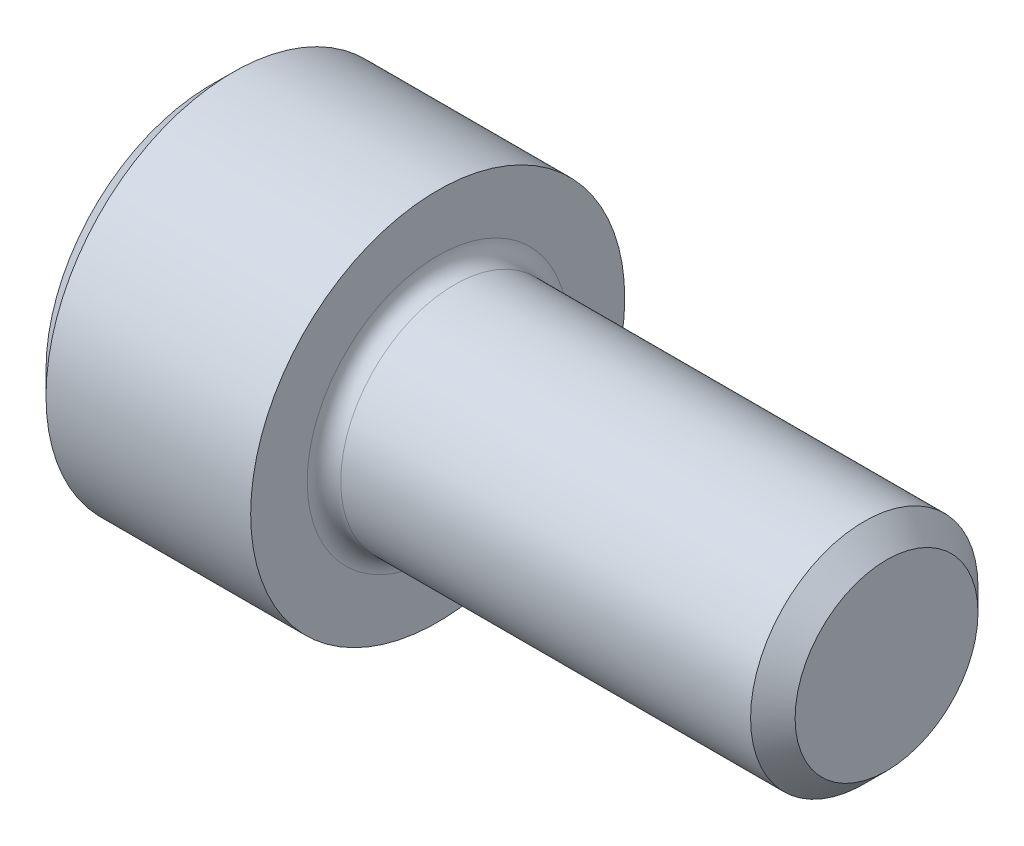
SolidWorks part; units mm, degrees
material "AISI 316 Annealed Stainless Steel Bar (SS)"
ref_plane "Plane1" through (0, 0, 0) normal (0, 0, 1) x (1, 0, 0)
ref_plane "Plane2" through (0, 0, 0) normal (0, 1, 0) x (1, 0, 0)
ref_plane "Plane3" through (0, 0, 0) normal (1, 0, 0) x (0, 0, -1)
sketch "BodySke" plane through (0, 0, 0) normal (0, 0, 1) x (1, 0, 0)
  line L0 (0, 0) -> (0, 3.4862)
  line L1 (0.4826, 3.9687) -> (4.826, 3.9687)
  line L2 (4.826, 3.9687) -> (4.826, 2.413)
  line L3 (4.826, 2.413) -> (13.8786, 2.413)
  line L4 (14.351, 1.9406) -> (14.351, 0)
  line L5 (14.351, 0) -> (0, 0)
  line L6 (-31.75, 0) -> (127, 0) construction
  line L7 (0, 3.4862) -> (0.4826, 3.9687)
  line L8 (14.351, 1.9406) -> (13.8786, 2.413)
  line L9 (0, -3.4862) -> (0.4826, -3.9688) construction
  line L10 (14.351, -1.9406) -> (13.8786, -2.413) construction
  line L11 (5.6185, 9.525) -> (5.6185, 3.175) construction
  line L12 (4.826, 9.525) -> (4.826, 3.175) construction
  line L13 (-23.749, 9.525) -> (-23.749, 3.175) construction
  dimension "Diameter" = 4.826
  dimension "Head_ht" = 4.826
  dimension "Length" = 9.525
  dimension "Body_ch_ang" = 45
  dimension "Head_dia" = 7.9375
  dimension "Head_ch_ang" = 45
  dimension "Head_side_ht" = 4.3434
  dimension "Minor_dia" = 3.8811
  dimension "Advance" = 0.7925
  dimension "Thread_nom" = 9.525
  dimension "Thread_length" = 38.1
revolve "Base-Revolve" add sketch "BodySke"
cosmetic thread "ThreadCosmetic" [suppressed]
fillet "Fillet1" radius 0.3556 1 edges at (4.826, 0, 2.413)
sketch "Sketch2" plane through (0, 0, 0) normal (0, 0, 1) x (1, 0, 0)
  line L0 (0, 1.985) -> (2.286, 1.985)
  line L1 (2.286, 1.985) -> (3.432, 0)
  line L2 (-31.75, 0) -> (127, 0) construction
  line L3 (3.432, 0) -> (0, 0)
  line L4 (0, 0) -> (0, 1.985)
  line L5 (0, 3.4862) -> (0, -3.4862) construction
  line L6 (0, 0) -> (47.625, 0) construction
  line L7 (4.826, -3.9687) -> (4.826, 3.9687) construction
  dimension "D1" = 1.985
  dimension "D2" = 60
  dimension "Wall_thickness" = 2.54
revolve "Hex-PreBroach" cut sketch "Sketch2" angle 360 about L6
sketch "Sketch3" plane through (0, 0, 0) normal (-1, 0, 0) x (0, 0.5, 0.866)
  line L0 (1.146, 1.985) -> (-1.146, 1.985)
  line L1 (-1.146, 1.985) -> (-2.2921, 0)
  line L2 (1.146, 1.985) -> (2.2921, 0)
  line L3 (1.146, -1.985) -> (2.2921, 0)
  line L4 (1.146, -1.985) -> (-1.146, -1.985)
  line L5 (-1.146, -1.985) -> (-2.2921, 0)
  dimension "D1" = 1.985
  dimension "D2" = 1.985
  dimension "Hex_size" = 3.97
extrude "Hex" cut sketch "Sketch3" against normal blind 2.286
sketch "Sketch4" plane through (0, 0, 0) normal (-1, 0, 0) x (0, 0, 1)
  line L0 (0, 0) -> (2.3876, 0)
  line L1 (0, 0) -> (6.1484, 3.5498) construction
  line L2 (0, 0) -> (1.1938, 2.0677)
  line L3 (1.9883, 0.576) -> (2.2704, 0.7389)
  line L4 (1.493, 1.4339) -> (1.7751, 1.5968)
  arc A0 (1.9883, 0.576) -> (1.493, 1.4339) centre (0, 0) ccw
  arc A1 (2.3876, 0) -> (2.2704, 0.7389) centre (0, 0) ccw
  arc A2 (1.1938, 2.0677) -> (1.7751, 1.5968) centre (0, 0) cw
  dimension "D1" = 30
  dimension "Spline_n_dim" = 4.1402
  dimension "Spline_m_dim" = 4.7752
  dimension "D2" = 60
  dimension "D3" = 0.4953
  dimension "Spline_p_dim" = 0.9906
extrude "Spline" [suppressed] cut sketch "Sketch4" against normal blind 2.286
pattern_circular "CirPattern1" [suppressed] count 6 every 60
sketch "Sketch5" plane through (0, 0, 0) normal (0, 0, 1) x (1, 0, 0)
  line L0 (-31.75, 0) -> (127, 0) construction
  line L2 (0, 3.4862) -> (0, -3.4862) construction
  circle A0 centre (1.651, 0) radius 0.5905
  dimension "Drilled_hole_dia" = 1.1811
  dimension "Drilled_hole_loc" = 1.651
extrude "Hole" [suppressed] cut sketch "Sketch5" against normal through all and the other way through all
pattern_circular "Drilled-4" [suppressed] count 2 every 60
pattern_circular "Drilled-6" [suppressed] count 3 every 60
sketch "ThdSchSke" plane through (0, 0, 0) normal (0, 0, 1) x (1, 0, 0)
  line L0 (5.6185, -1.9406) -> (5.2877, -2.413)
  line L1 (5.6185, -1.9406) -> (5.9493, -2.413)
  line L2 (5.9493, -2.413) -> (5.9493, -3.0163)
  line L3 (-3.175, 0) -> (5.1513, 0) construction
  line L5 (5.9493, -3.0163) -> (5.2877, -3.0163)
  line L6 (5.2877, -3.0163) -> (5.2877, -2.413)
  line L7 (0, 3.4862) -> (0, -3.4862) construction
  dimension "Thread_minor" = 3.8811
  dimension "Diameter" = 4.826
  dimension "Start" = 5.6185
  dimension "SideAngle" = 55
  dimension "VeeAngle" = 70
  dimension "Overcut" = 6.0325
revolve "ThreadSchematic" [suppressed] cut sketch "ThdSchSke" angle 360 about L3
pattern_linear "ThdSchPat" [suppressed]
equation "\"D2@Sketch3\" = \"Hex_size@Sketch3\" / 2"
equation "\"D1@Sketch3\" = \"Hex_size@Sketch3\" / 2"
equation "\"D1@Sketch2\" = \"Hex_size@Sketch3\" / 2"
equation "\"D3@Sketch4\" = \"Spline_p_dim@Sketch4\" / 2"
equation "\"Thread_minor@ThreadCosmetic\"  =  \"Minor_dia@BodySke\""
equation "\"D2@CirPattern1\" = 360 / \"Num_teeth@CirPattern1\""
equation "\"Wall_thickness@Sketch2\" = \"Head_ht@BodySke\" - \"Key_eng@Hex\""
equation "\"Thread_length@ThreadCosmetic\" = ((sgn( (\"Length@BodySke\" - \"Advance@BodySke\" ) - \"Thread_nom@BodySke\" )-1)*( (\"Length@BodySke\" - \"Advance@BodySke\" ) - \"Thread_nom@BodySke\" ))/-2+ \"Thread_nom@BodySke\""
equation "\"Thread_minor@ThdSchSke\" = \"Minor_dia@BodySke\""
equation "\"Diameter@ThdSchSke\" = \"Diameter@BodySke\""
equation "\"Overcut@ThdSchSke\" = \"Diameter@BodySke\" * 1.25"
equation "\"Start@ThdSchSke\" = \"Head_ht@BodySke\" + \"Length@BodySke\" - \"Thread_length@ThreadCosmetic\"  '---Non-countersunk---"
equation "\"Num_threads@ThdSchPat\" = int( \"Thread_length@ThreadCosmetic\" / \"Advance@BodySke\" + 0.999 )  + 1"
equation "\"Advance@ThdSchPat\" = \"Thread_length@ThreadCosmetic\" /  (\"Num_threads@ThdSchPat\" - 1) 'relax it"
equation "\"Num_threads@ThdSchPat\" = \"Num_threads@ThdSchPat\" - sgn( \"Num_threads@ThdSchPat\" - 1) '---chamfered tips only---"
